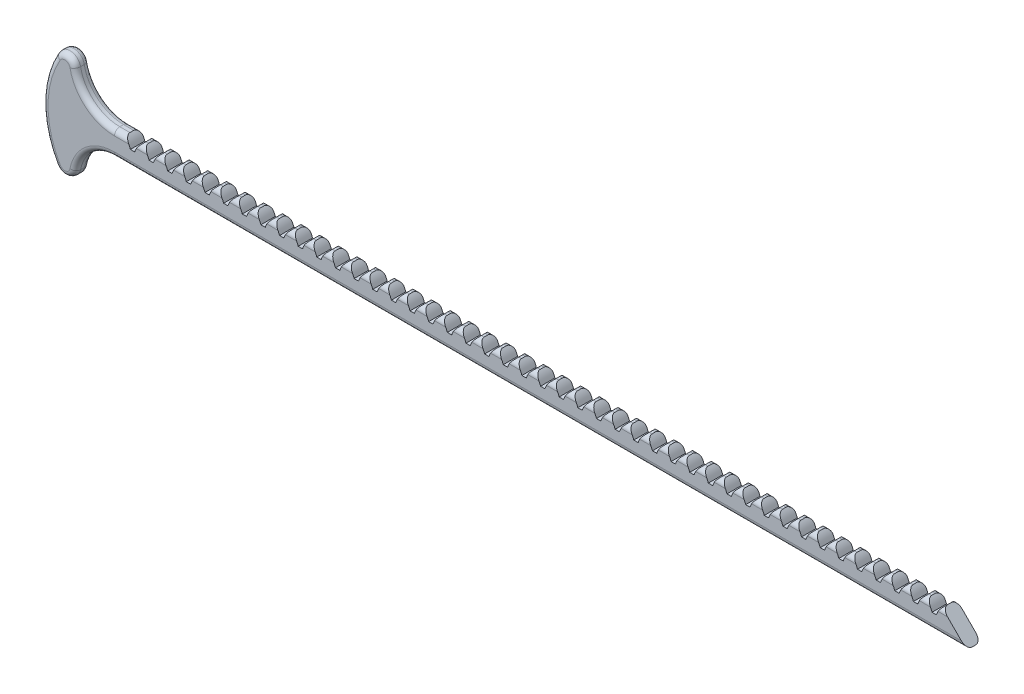
SolidWorks part; units mm, degrees
material "Plain Carbon Steel"
ref_plane "Front Plane" through (0, 0, 0) normal (0, 0, 1) x (1, 0, 0)
ref_plane "Top Plane" through (0, 0, 0) normal (0, 1, 0) x (1, 0, 0)
ref_plane "Right Plane" through (0, 0, 0) normal (1, 0, 0) x (0, 0, -1)
sketch "Sketch1" plane through (0, 0, 0) normal (0, 0, 1) x (1, 0, 0)
  line L0 (-101.6, 0) -> (101.6, 0)
  line L1 (101.6, 0) -> (95.758, 5.842)
  line L2 (95.758, 5.842) -> (-101.6, 5.842)
  arc A0 (-101.6, 5.842) -> (-110.9525, 13.5623) centre (-101.6, 15.367) cw
  arc A2 (-110.9525, -7.7203) -> (-101.6, 0) centre (-101.6, -9.525) cw
  arc A4 (-115.6462, 14.351) -> (-115.6462, -8.509) centre (-95.8488, 2.921) ccw
  arc A5 (-115.6462, -8.509) -> (-110.9525, -7.7203) centre (-113.4465, -7.239) ccw
  arc A6 (-110.9525, 13.5623) -> (-115.6462, 14.351) centre (-113.4465, 13.081) ccw
  point P10 (0, 0)
  point P14 (98.679, 2.921)
  dimension "D1" = 45
  dimension "D2" = 5.842
  dimension "D4" = 2.54
  dimension "D5" = 9.525
  dimension "D6" = 22.86
  dimension "D7" = 25.4
  dimension "D3" = 203.2
extrude "Boss-Extrude1" add sketch "Sketch1" along normal mid plane 3.429
fillet "Fillet1" radius 1.27 14 edges at (-2.921, 5.842, 1.7145) (0, 0, 1.7145) (-107.6636, -2.1794, 1.7145) (-113.0255, -9.7439, 1.7145) (-118.7088, 2.921, 1.7145) (-113.0255, 15.5859, 1.7145) (0, 0, -1.7145) (-2.921, 5.842, -1.7145) (-107.6636, 8.0214, -1.7145) (-113.0255, 15.5859, -1.7145) (-118.7088, 2.921, -1.7145) (-113.0255, -9.7439, -1.7145) (-107.6636, -2.1794, -1.7145) (-107.6636, 8.0214, 1.7145)
sketch "Sketch3" plane through (0, 0, 0) normal (0, 0, 1) x (1, 0, 0)
  line L0 (-101.6, 5.842) -> (95.758, 5.842) construction
  line L1 (93.3309, 3.683) -> (94.3751, 3.683)
  line L2 (91.948, 5.842) -> (95.758, 5.842)
  line L3 (93.853, 5.842) -> (93.853, 3.683) construction
  arc A0 (95.758, 5.842) -> (94.3751, 3.683) centre (99.2058, 2.1112) ccw
  arc A1 (91.948, 5.842) -> (93.3309, 3.683) centre (88.5002, 2.1112) cw
  dimension "D1" = 5.08
  dimension "D2" = 2.159
  dimension "D3" = 3.81
  dimension "D4" = 1.0442
extrude "Cut-Extrude1" cut sketch "Sketch3" against normal through all both and the other way through all
pattern_linear "LPattern1" count 44 spacing 4.445 along (-1, 0, 0) of "Cut-Extrude1"
